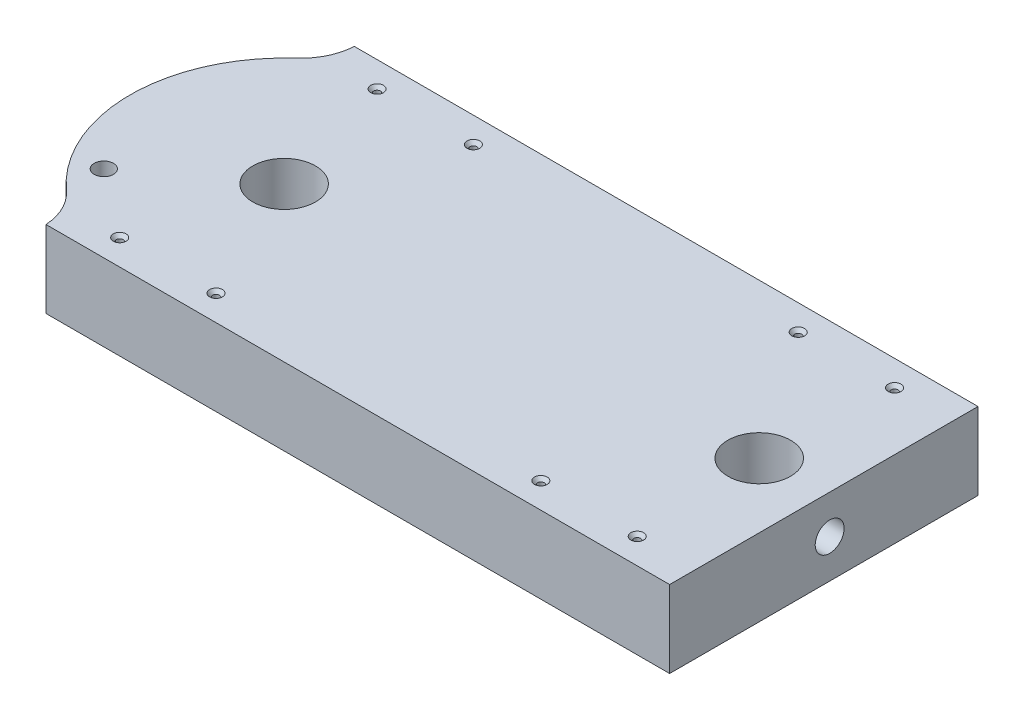
SolidWorks part; units mm, degrees
material "Pine"
ref_plane "Front Plane" through (0, 0, 0) normal (0, 0, 1) x (1, 0, 0)
ref_plane "Top Plane" through (0, 0, 0) normal (0, 1, 0) x (1, 0, 0)
ref_plane "Right Plane" through (0, 0, 0) normal (1, 0, 0) x (0, 0, -1)
other "Configuration Table"
sketch "Sketch1" plane through (0, 0, 0) normal (0, 1, 0) x (1, 0, 0)
  line L0 (0, -101.6) -> (-766.6236, -101.6) construction
  line L2 (0, 0) -> (0, -203.2)
  line L5 (-410.9201, 0) -> (-457.2, 0) construction
  line L7 (0, -203.2) -> (0, 0)
  line L9 (-457.2, -203.2) -> (-457.2, -137.1202) construction
  line L10 (-410.9201, -203.2) -> (-457.2, -203.2) construction
  line L11 (-457.2, -66.0798) -> (-457.2, 0) construction
  line L12 (-457.2, -137.1202) -> (-457.2, -66.0798) construction
  line L13 (-355.6, -101.6) -> (-355.6, -309.6499) construction
  line L14 (0, 0) -> (-410.9201, 0)
  line L15 (0, -203.2) -> (-410.9201, -203.2)
  arc A0 (-423.4899, -26.0122) -> (-423.4899, -177.1878) centre (-355.6, -101.6) ccw
  arc A1 (-423.4899, -26.0122) -> (-410.9201, 0) centre (-448.9486, 2.3333) ccw
  arc A2 (-410.9201, -203.2) -> (-423.4899, -177.1878) centre (-448.9486, -205.5333) ccw
  circle A3 centre (-355.6, -101.6) radius 101.6 construction
  circle A6 centre (-448.9486, 2.3333) radius 38.1 construction
  circle A7 centre (-448.9486, -205.5333) radius 38.1 construction
  dimension "D3" = 101.6
  dimension "D4" = 76.2
  dimension "D5" = 203.2
  dimension "D1" = 457.2
  dimension "D2" = 203.2
  dimension "D6" = 101.6
extrude "Boss-Extrude1" add sketch "Sketch1" along normal blind 50.8
sketch "Sketch2" plane through (0, 0, 203.2) normal (0, 0, 1) x (1, 0, 0)
  line L2 (-410.9201, 25.4) -> (-306.9829, 25.4) construction
  line L3 (-410.9201, 50.8) -> (-410.9201, 0) construction
  circle A0 centre (-370.5922, 25.4) radius 6.35
  dimension "D1" = 12.7
extrude "Cut-Extrude1" [suppressed] cut sketch "Sketch2" against normal blind 50.8
sketch "Sketch3" plane through (0, 0, 0) normal (1, 0, 0) x (0, 0, -1)
  line L0 (0, 25.4) -> (-248.5455, 25.4) construction
  line L1 (0, 50.8) -> (0, 0) construction
  line L2 (-101.6, 50.8) -> (-101.6, -50.7551) construction
  line L3 (0, 50.8) -> (-203.2, 50.8) construction
  circle A1 centre (-30.0783, 25.4) radius 6.35
  dimension "D1" = 12.7
extrude "Cut-Extrude2" [suppressed] cut sketch "Sketch3" against normal blind 50.8
sketch "Sketch4" plane through (0, 50.8, 0) normal (0, 1, 0) x (1, 0, 0)
  line L0 (0, -101.6) -> (-662.5845, -101.6) construction
  line L1 (0, 0) -> (0, -203.2) construction
sketch "Sketch5" plane through (0, 0, 203.2) normal (0, 0, 1) x (1, 0, 0)
  line L0 (0, 25.4) -> (-296.3789, 25.4) construction
  line L1 (0, 50.8) -> (0, 0) construction
  circle A0 centre (-66.3194, 25.4) radius 8.4944
  dimension "D1" = 66.3194
hole_wizard "5/8-11 Tapped Hole1" [suppressed] positions "Sketch6" profile "Sketch7" tap size "5/8-11" standard "ANSI Inch"
sketch "Sketch6" plane through (0, 0, 203.2) normal (0, 0, 1) x (1, 0, 0)
  point P0 (-66.3194, 12.7)
sketch "Sketch7" plane through (-66.3194, 12.7, 203.2) normal (1, 0, 0) x (0, -1, 0)
  line L0 (0, 0) -> (0, 22.225)
  line L1 (0, 22.225) -> (6.7462, 18.1715)
  line L2 (6.7462, 18.1715) -> (6.7462, 0)
  line L5 (6.7462, 0) -> (0, 0)
  line L10 (0, 22.225) -> (-6.7462, 18.1715) construction
  line L11 (0, -6.35) -> (0, 107.95) construction
  dimension "Tap Drill Dia." = 13.4925
  dimension "Tap Drill Depth" = 22.225
  dimension "Drill Angle" = 118
sketch "Sketch8" plane through (0, 0, 203.2) normal (0, 0, 1) x (1, 0, 0)
  line L0 (0, 50.8) -> (-662.5845, 50.8) construction
  line L1 (0, 0) -> (-132.6388, 0)
  line L2 (0, 0) -> (0, 50.8)
  line L3 (0, 50.8) -> (-132.6388, 50.8)
  line L4 (-132.6388, 0) -> (-132.6388, 50.8)
  dimension "D1" = 132.6388
extrude "Cut-Extrude3" [suppressed] cut sketch "Sketch8" against normal blind 38.1
hole_wizard "CSK for #8 Flat Head Machine Screw (100)1" positions "Sketch10" profile "Sketch12" countersink size "#8" standard "ANSI Inch" end condition through all
sketch "Sketch10" plane through (0, 50.8, 0) normal (0, 1, 0) x (1, 0, 0)
  line L0 (0, -203.2) -> (-410.9201, -203.2) construction
  point P0 (-379.1701, -186.3852)
  point P2 (-315.6701, -186.3852)
  dimension "D1" = 31.75
  dimension "D2" = 63.5
  dimension "D3" = 16.8148
sketch "Sketch12" plane through (-379.1701, 50.8, 186.3852) normal (1, 0, 0) x (0, 0, 1)
  line L0 (0, 0) -> (0, 50.8)
  line L1 (0, 50.8) -> (2.2479, 50.8)
  line L2 (2.2479, 50.8) -> (2.2479, 2.2645)
  line L3 (2.2479, 2.2645) -> (4.2164, 0)
  line L5 (4.2164, 0) -> (0, 0)
  line L6 (-2.2479, 2.2645) -> (-4.2164, 0) construction
  line L11 (0, -6.35) -> (0, 107.95) construction
  dimension "Thru Hole Dia." = 4.4958
  dimension "Thru Hole Depth" = 50.8
  dimension "Near C'Sink Dia." = 8.4328
  dimension "Near C'Sink Angle" = 82
ref_plane "Plane1" through (0, 0, 101.6) normal (0, 0, 1) x (1, 0, 0)
mirror "Mirror1" about plane through (0, 0, 101.6) normal (0, 0, 1) of "CSK for #8 Flat Head Machine Screw (100)1"
sketch "Sketch13" plane through (0, 50.8, 0) normal (0, 1, 0) x (1, 0, 0)
  line L0 (-208.661, 50.579) -> (-208.661, -369.1658) construction
  line L1 (0, 0) -> (0, -203.2) construction
  dimension "D1" = 410.9201
  dimension "D2" = 208.661
ref_plane "Plane2" through (-208.661, 0, 0) normal (1, 0, 0) x (0, 0, -1)
mirror "Mirror2" about plane through (-208.661, 0, 0) normal (1, 0, 0) of "Mirror1", "CSK for #8 Flat Head Machine Screw (100)1"
sketch "Sketch18" plane through (0, 50.8, 0) normal (0, 1, 0) x (1, 0, 0)
  line L0 (0, 0) -> (0, -203.2) construction
  line L2 (0, -203.2) -> (-410.9201, -203.2) construction
  circle A0 centre (-57.15, -146.05) radius 57.15 construction
  dimension "D1" = 114.3
sketch "Sketch14" plane through (0, 50.8, 0) normal (0, 1, 0) x (1, 0, 0)
  line L0 (0, -203.2) -> (-410.9201, -203.2) construction
  circle A0 centre (-423.6201, -152.4) radius 6.35
  dimension "D1" = 12.7
  dimension "D3" = 12.7
  dimension "D2" = 50.8
extrude "Cut-Extrude4" cut sketch "Sketch14" against normal through all
sketch "Sketch15" plane through (0, 50.8, 0) normal (0, 1, 0) x (1, 0, 0)
  line L0 (0, -101.6) -> (-662.5845, -101.6) construction
  circle A0 centre (-355.6, -101.6) radius 165.1 construction
  arc A1 (-423.4899, -26.0122) -> (-423.4899, -177.1878) centre (-355.6, -101.6) ccw construction
  circle A2 centre (-355.6, -101.6) radius 20.6375
  dimension "D1" = 330.2
  dimension "D2" = 41.275
extrude "Cut-Extrude5" cut sketch "Sketch15" against normal through all
sketch "Sketch16" plane through (0, 50.8, 0) normal (0, 1, 0) x (1, 0, 0)
  line L0 (0, -101.6) -> (-662.5845, -101.6) construction
  line L1 (0, 0) -> (0, -203.2) construction
  circle A0 centre (-42.545, -101.6) radius 20.6375
  circle A3 centre (-42.545, -101.6) radius 57.15 construction
  dimension "D1" = 41.275
  dimension "D2" = 42.545
extrude "Cut-Extrude6" cut sketch "Sketch16" against normal through all
sketch "Sketch17" plane through (0, 50.8, 0) normal (0, 1, 0) x (1, 0, 0)
  line L0 (-520.7, -101.6) -> (-520.7, -202.534) construction
  line L1 (0, -101.6) -> (0, -282.4079) construction
  circle A0 centre (-355.6, -101.6) radius 165.1 construction
  circle A1 centre (-42.545, -101.6) radius 82.55 construction
  dimension "D1" = 330.2
  dimension "D2" = 165.1
  dimension "D3" = 520.7
sketch "Sketch19" plane through (0, 50.8, 0) normal (0, 1, 0) x (1, 0, 0)
  line L0 (-355.6, -76.2) -> (-42.545, -76.2) construction
  line L1 (-355.6, -127) -> (-42.545, -127) construction
  line L2 (-355.6, -130.9624) -> (-42.545, -130.9624) construction
  line L3 (-355.6, -72.2376) -> (-42.545, -72.2376) construction
  arc A0 (-355.6, -76.2) -> (-355.6, -127) centre (-355.6, -101.6) ccw construction
  arc A1 (-42.545, -127) -> (-42.545, -76.2) centre (-42.545, -101.6) ccw construction
  circle A3 centre (-42.545, -101.6) radius 20.6375 construction
  arc A4 (-355.6, -72.2376) -> (-355.6, -130.9624) centre (-355.6, -101.6) ccw construction
  arc A5 (-42.545, -130.9624) -> (-42.545, -72.2376) centre (-42.545, -101.6) ccw construction
  dimension "D1" = 50.8
  dimension "D2" = 50.8
  dimension "D3" = 3.9624
hole_wizard "5/8 (0.75) Diameter Hole1" positions "Sketch20" profile "Sketch21" hole size "5/8" standard "ANSI Inch"
sketch "Sketch20" plane through (0, 0, 0) normal (1, 0, 0) x (0, 0, -1)
  line L7 (0, 25.4) -> (-54.4815, 25.4) construction
  line L8 (0, 50.8) -> (0, 0) construction
  point P0 (-97.7392, 25.4)
  dimension "D1" = 97.7392
sketch "Sketch21" plane through (0, 25.4, 97.7392) normal (0, 1, 0) x (0, 0, -1)
  line L0 (0, 0) -> (0, 38.6842)
  line L1 (0, 38.6842) -> (9.525, 32.961)
  line L2 (9.525, 32.961) -> (9.525, 0)
  line L5 (9.525, 0) -> (0, 0)
  line L10 (0, 38.6842) -> (-9.525, 32.961) construction
  line L11 (0, -6.35) -> (0, 107.95) construction
  dimension "Hole Dia." = 19.05
  dimension "Hole Depth" = 38.6842
  dimension "Drill Angle" = 118
